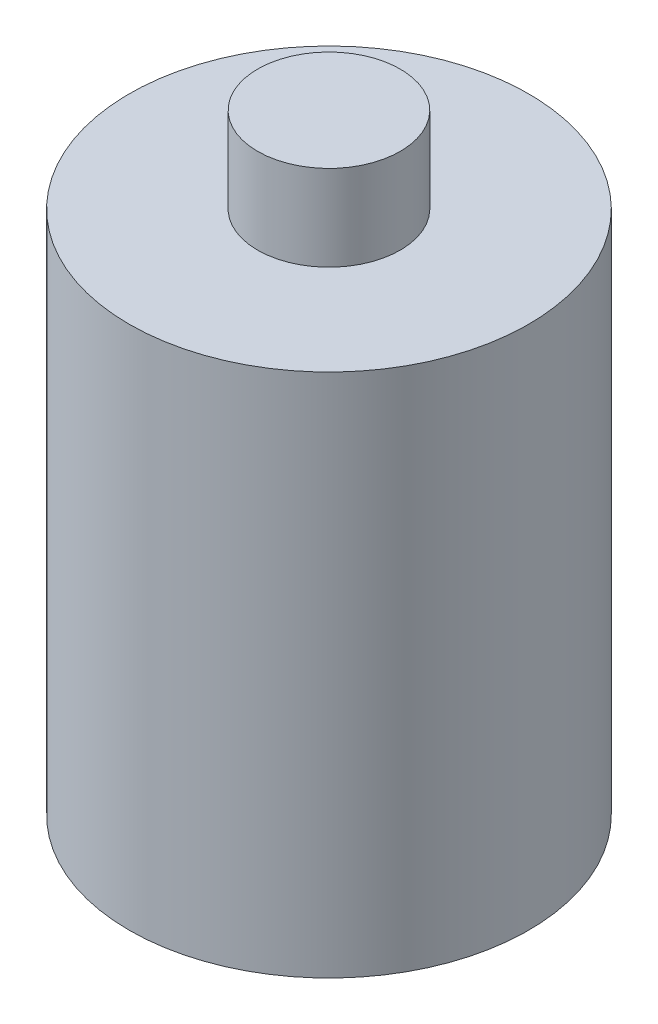
SolidWorks part; units mm, degrees
ref_plane "前视基准面" through (0, 0, 0) normal (0, 0, 1) x (1, 0, 0)
ref_plane "上视基准面" through (0, 0, 0) normal (0, 1, 0) x (1, 0, 0)
ref_plane "右视基准面" through (0, 0, 0) normal (1, 0, 0) x (0, 0, -1)
other "Configuration Table"
sketch "草图1" plane through (0, 0, 0) normal (0, 1, 0) x (1, 0, 0)
  circle A0 centre (0, 0) radius 7
extrude "凸台-拉伸1" add sketch "草图1" along normal blind 18.4
sketch "草图2" plane through (0, 18.4, 0) normal (0, 1, 0) x (1, 0, 0)
  circle A0 centre (0, 0) radius 2.5
extrude "凸台-拉伸2" add sketch "草图2" along normal blind 3
